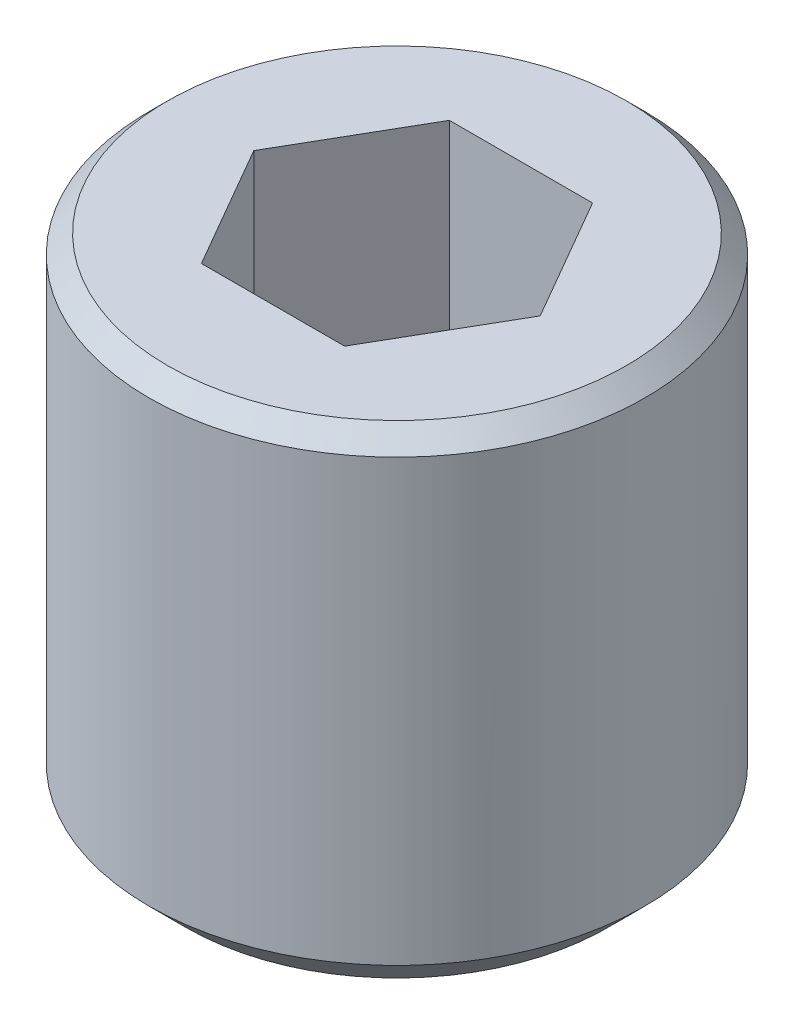
SolidWorks part; units mm, degrees
material "acero"
ref_plane "Alzado" through (0, 0, 0) normal (0, 0, 1) x (1, 0, 0)
ref_plane "Planta" through (0, 0, 0) normal (0, 1, 0) x (1, 0, 0)
ref_plane "Vista lateral" through (0, 0, 0) normal (1, 0, 0) x (0, 0, -1)
sketch "Croquis1" plane through (0, 0, 0) normal (0, 0, 1) x (1, 0, 0)
  line L0 (0, 0) -> (0, -60.9498) construction
  line L1 (0, 0) -> (2, 0)
  line L4 (2, 0) -> (2, -4)
  line L5 (2, -4) -> (0, -4)
  line L6 (0, -4) -> (0, 0)
  dimension "D1" = 4
  dimension "D4" = 4
revolve "Revolución1" add sketch "Croquis1" angle 360 about L0
cosmetic thread "Rosca cosmética1" parameters "D2"=3.22
sketch "Croquis3" plane through (0, 0, 0) normal (0, 1, 0) x (1, 0, 0)
  line L1 (-0.5774, 1) -> (-1.1547, 0)
  line L2 (-1.1547, 0) -> (-0.5774, -1)
  line L3 (-0.5774, -1) -> (0.5774, -1)
  line L4 (0.5774, -1) -> (1.1547, 0)
  line L5 (1.1547, 0) -> (0.5774, 1)
  line L6 (0.5774, 1) -> (-0.5774, 1)
  circle A0 centre (0, 0) radius 1 construction
  dimension "D1" = 2
extrude "Cortar-Extruir2" cut sketch "Croquis3" against normal blind 2
chamfer "Chaflán3" distance 0.3 angle 45
chamfer "Chaflán4" distance 0.15 angle 45
